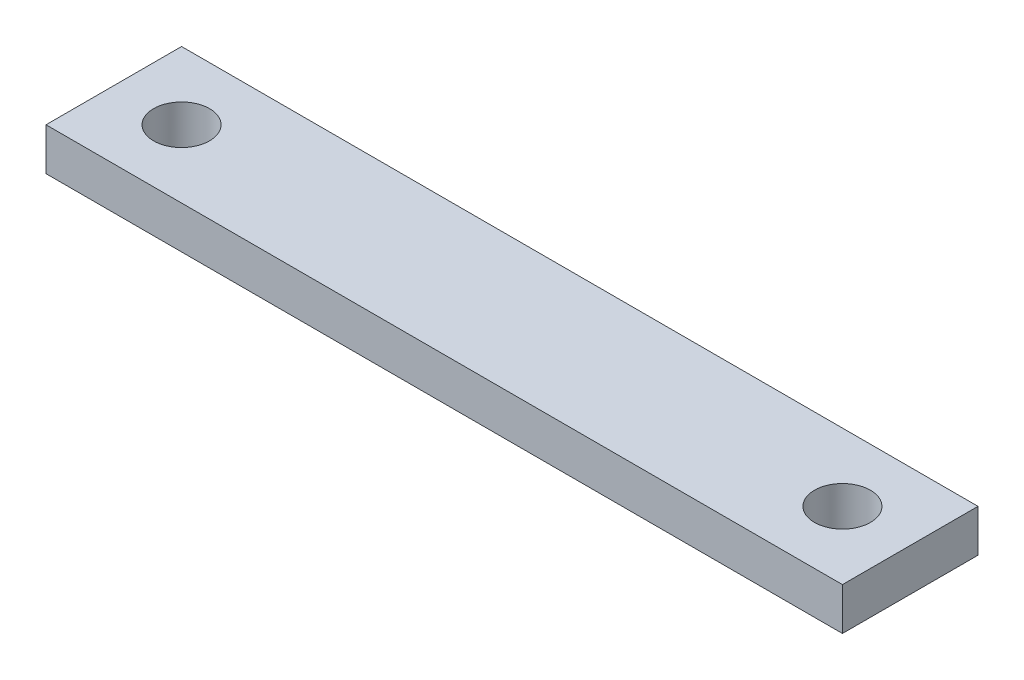
SolidWorks part; units mm, degrees
ref_plane "Front Plane" through (0, 0, 0) normal (0, 0, 1) x (1, 0, 0)
ref_plane "Top Plane" through (0, 0, 0) normal (0, 1, 0) x (1, 0, 0)
ref_plane "Right Plane" through (0, 0, 0) normal (1, 0, 0) x (0, 0, -1)
sketch "Sketch1" plane through (0, 0, 0) normal (0, 1, 0) x (1, 0, 0)
  line L1 (0, 0) -> (47, 0)
  line L2 (0, 0) -> (0, 8)
  line L3 (0, 8) -> (47, 8)
  line L4 (47, 0) -> (47, 8)
  dimension "D1" = 47
  dimension "D2" = 8
extrude "Boss-Extrude1" add sketch "Sketch1" along normal blind 2.5
sketch "Sketch2" plane through (0, 0, 0) normal (0, 1, 0) x (1, 0, 0)
  line L0 (0, 8) -> (0, 0) construction
  line L1 (0, 0) -> (47, 0) construction
  circle A0 centre (4, 4) radius 1.65
  circle A1 centre (43, 4) radius 1.65
  dimension "D1" = 3.3
  dimension "D2" = 4
  dimension "D3" = 4
  dimension "D4" = 2
extrude "Cut-Extrude1" cut sketch "Sketch2" along normal up to surface (2.5 mm away) up to face at (23.5, 2.5, -4)
